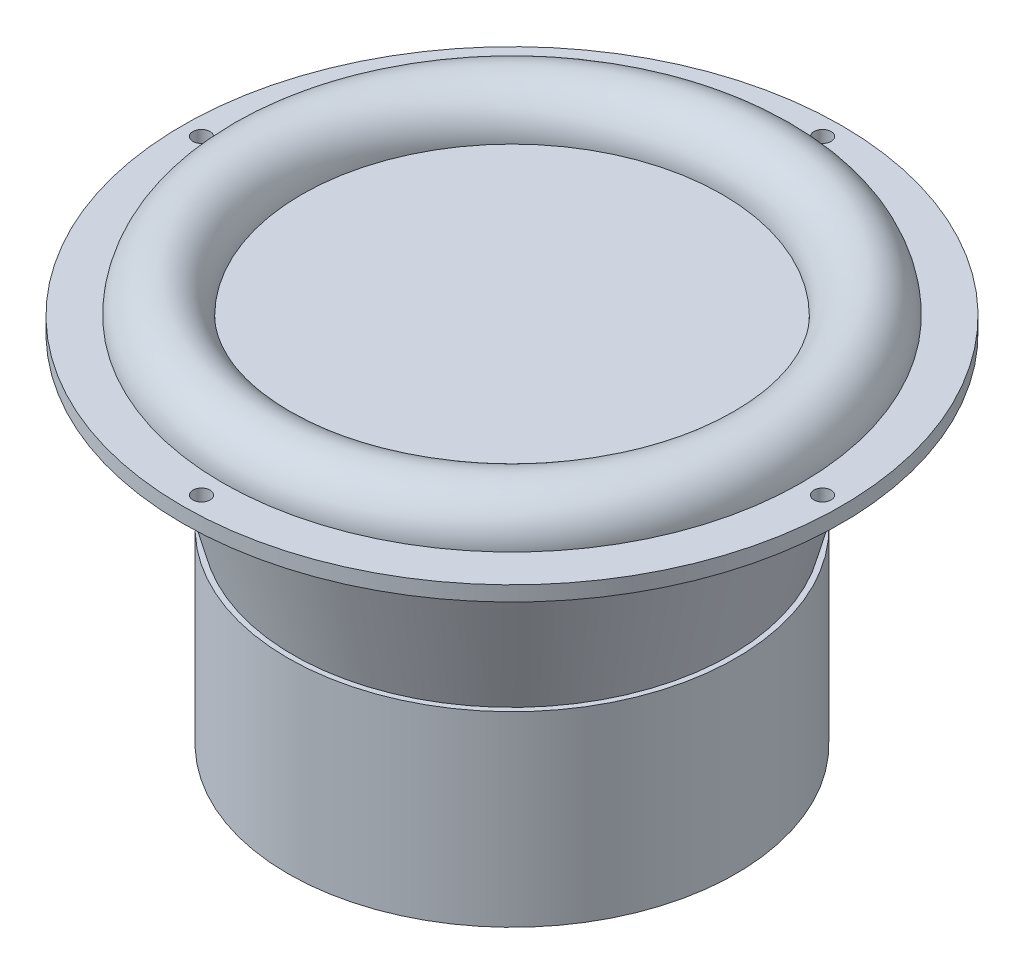
SolidWorks part; units mm, degrees
ref_plane "Front Plane" through (0, 0, 0) normal (0, 0, 1) x (1, 0, 0)
ref_plane "Top Plane" through (0, 0, 0) normal (0, 1, 0) x (1, 0, 0)
ref_plane "Right Plane" through (0, 0, 0) normal (1, 0, 0) x (0, 0, -1)
sketch "Sketch1" plane through (0, 0, 0) normal (0, 0, 1) x (1, 0, 0)
  line L0 (0, -46.3085) -> (0, 99.4) construction
  line L1 (0, 99.4) -> (56.3, 99.4)
  line L2 (77.5, 99.4) -> (88.25, 99.4)
  line L3 (88.25, 99.4) -> (88.25, 95.4)
  line L4 (88.25, 95.4) -> (70.75, 95.4)
  line L5 (70.75, 95.4) -> (58.5851, 50)
  line L6 (58.5851, 50) -> (60, 50)
  line L7 (60, 50) -> (60, 0)
  line L8 (60, 0) -> (0, 0)
  line L9 (0, 0) -> (0, 99.4)
  arc A0 (77.5, 99.4) -> (56.3, 99.4) centre (66.9, 99.4) ccw
  point P12 (0, 98.7149)
  point P14 (0, 0)
  point P15 (0, 99.4)
  point P16 (0, 98.8031)
  dimension "D7" = 110
  dimension "D1" = 176.5
  dimension "D2" = 155
  dimension "D3" = 4
  dimension "D4" = 141.5
  dimension "D5" = 15
  dimension "D6" = 50
  dimension "D8" = 99.4
  dimension "D9" = 60
revolve "Revolve1" add sketch "Sketch1" angle 360 about L0
hole_wizard "Ø4.6 (4.6) Diameter Hole1" positions "Sketch2" profile "Sketch3" hole size "Ø4.6" standard "ANSI Metric" end condition through all
sketch "Sketch2" plane through (0, 99.4, 0) normal (0, 1, 0) x (1, 0, 0)
  circle A0 centre (0, 0) radius 83.15
  point P5 (-83.15, 0)
  point P7 (0, 83.15)
  point P9 (83.15, 0)
  point P11 (0, -83.15)
  dimension "D1" = 166.3
sketch "Sketch3" plane through (0, 99.4, 83.15) normal (1, 0, 0) x (0, 0, 1)
  line L0 (0, 0) -> (0, 99.4)
  line L1 (0, 99.4) -> (2.3, 99.4)
  line L2 (2.3, 99.4) -> (2.3, 0)
  line L5 (2.3, 0) -> (0, 0)
  line L11 (0, -6.35) -> (0, 107.95) construction
  dimension "Thru Hole Dia." = 4.6
  dimension "Thru Hole Depth" = 99.4
